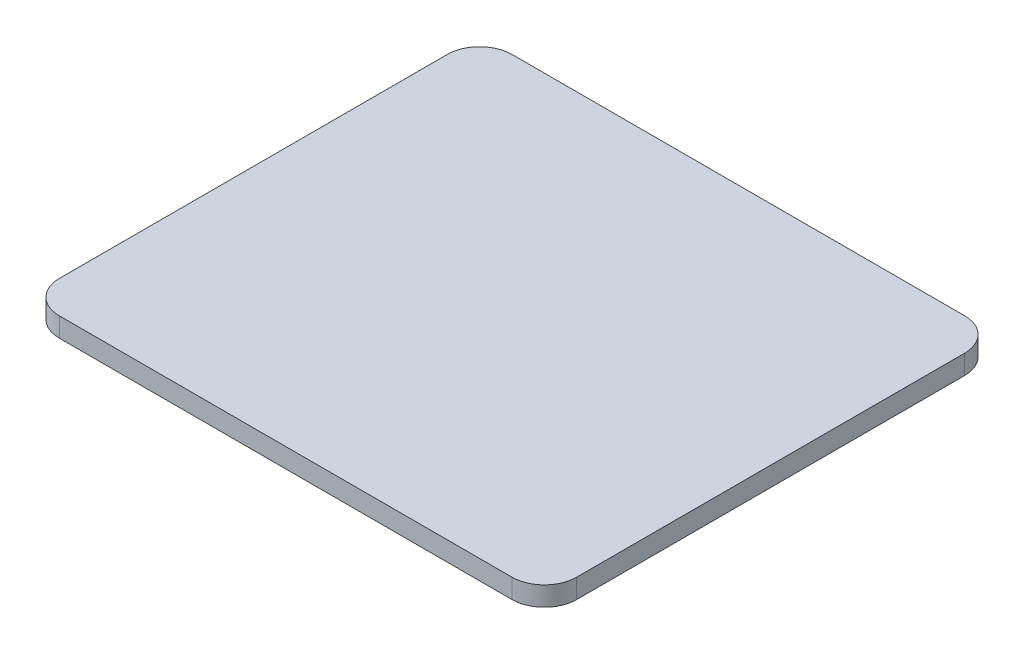
SolidWorks part; units mm, degrees
material "ABS"
ref_plane "Alzado" through (0, 0, 0) normal (0, 0, 1) x (1, 0, 0)
ref_plane "Planta" through (0, 0, 0) normal (0, 1, 0) x (1, 0, 0)
ref_plane "Vista lateral" through (0, 0, 0) normal (1, 0, 0) x (0, 0, -1)
sketch "Croquis2" plane through (0, 0, 0) normal (1, 0, 0) x (0, 0, -1)
  line L0 (-5, 0) -> (-5, 20)
  line L1 (5, 0) -> (5, 20)
  line L2 (-5, 20) -> (5, 20)
  circle A0 centre (0, 0) radius 1
  arc A1 (-5, 0) -> (5, 0) centre (0, 0) ccw
  dimension "D1" = 2
  dimension "D2" = 10
  dimension "D3" = 20
extrude "Saliente-Extruir1" add sketch "Croquis2" along normal blind 7
sketch "Croquis3" plane through (0, 20, 0) normal (0, 1, 0) x (1, 0, 0)
  line L0 (7.1025, 35) -> (7.1025, -35) construction
  line L1 (-27.8975, -35) -> (42.1025, -35)
  line L2 (-32.8975, -30) -> (-32.8975, 30)
  line L3 (-27.8975, 35) -> (42.1025, 35)
  line L4 (47.1025, -30) -> (47.1025, 30)
  line L5 (-32.8975, 0) -> (47.1025, 0) construction
  arc A0 (42.1025, 35) -> (47.1025, 30) centre (42.1025, 30) cw
  arc A1 (42.1025, -35) -> (47.1025, -30) centre (42.1025, -30) ccw
  arc A2 (-27.8975, -35) -> (-32.8975, -30) centre (-27.8975, -30) cw
  arc A3 (-32.8975, 30) -> (-27.8975, 35) centre (-27.8975, 30) cw
  point P6 (47.1025, 35)
  point P11 (-32.8975, -35)
  point P14 (-32.8975, 35)
  dimension "D3" = 5
  dimension "D1" = 80
  dimension "D2" = 70
extrude "Saliente-Extruir2" add sketch "Croquis3" along normal blind 3
sketch "Croquis4" plane through (7, 0, 0) normal (1, 0, 0) x (0, 0, -1)
  circle A0 centre (0, 0) radius 2.5
  dimension "D1" = 5
extrude "Cortar-Extruir1" cut sketch "Croquis4" against normal blind 2.6
sketch "Croquis5" plane through (0, 0, 0) normal (-1, 0, 0) x (0, 0, 1)
  circle A0 centre (0, 0) radius 2.6
  dimension "D1" = 5.2
extrude "Cortar-Extruir3" cut sketch "Croquis5" against normal blind 2.2
